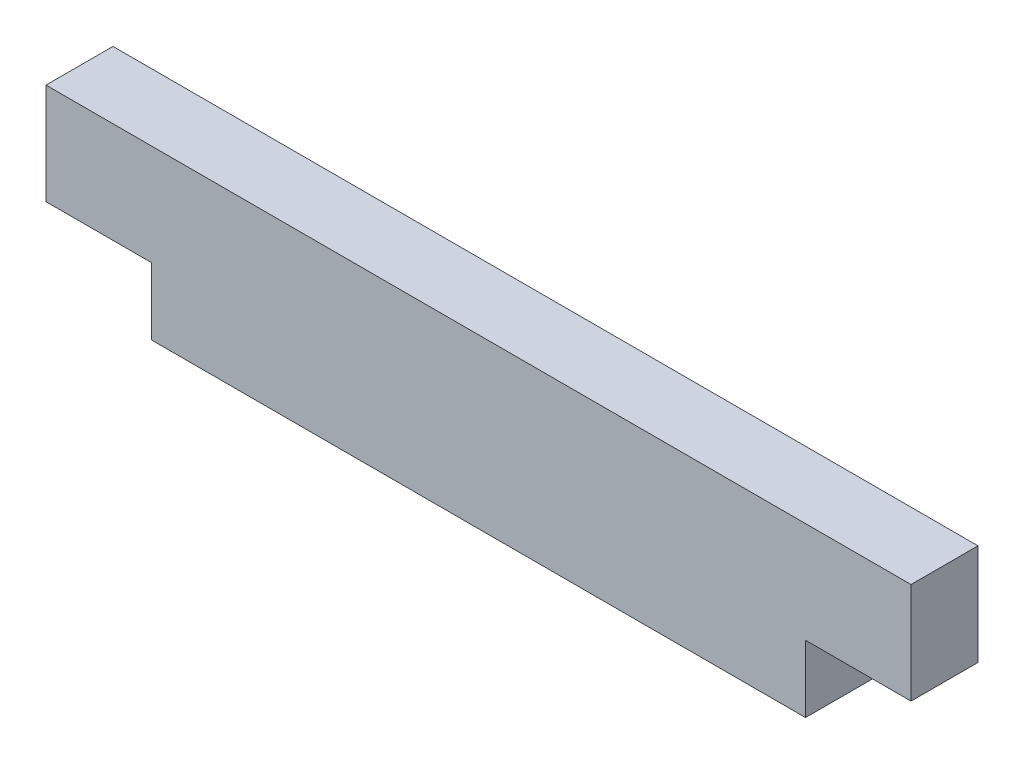
SolidWorks part; units mm, degrees
ref_plane "Front Plane" through (0, 0, 0) normal (0, 0, 1) x (1, 0, 0)
ref_plane "Top Plane" through (0, 0, 0) normal (0, 1, 0) x (1, 0, 0)
ref_plane "Right Plane" through (0, 0, 0) normal (1, 0, 0) x (0, 0, -1)
sketch "Sketch1" plane through (0, 0, 0) normal (0, 0, 1) x (1, 0, 0)
  line L1 (-20.5, -2.394) -> (20.5, -2.394)
  line L2 (-20.5, -2.394) -> (-20.5, 2.394)
  line L3 (-20.5, 2.394) -> (20.5, 2.394)
  line L4 (20.5, -2.394) -> (20.5, 2.394)
  line L5 (-20.5, -2.394) -> (20.5, 2.394) construction
  line L6 (-20.5, 2.394) -> (20.5, -2.394) construction
  line L7 (-15.5, -2.394) -> (-3.5, -2.394)
  line L8 (-15.5, -2.394) -> (-15.5, -5.569)
  line L9 (-15.5, -5.569) -> (-3.5, -5.569)
  line L10 (-3.5, -2.394) -> (-3.5, -5.569)
  line L11 (3.5, -2.394) -> (15.5, -2.394)
  line L12 (3.5, -2.394) -> (3.5, -5.569)
  line L13 (3.5, -5.569) -> (15.5, -5.569)
  line L14 (15.5, -2.394) -> (15.5, -5.569)
  point P0 (0, 0)
  dimension "D1" = 4.788
  dimension "D2" = 41
  dimension "D3" = 3.175
  dimension "D4" = 3.175
  dimension "D5" = 12
  dimension "D6" = 12
  dimension "D7" = 5
  dimension "D8" = 5
extrude "Boss-Extrude1" add sketch "Sketch1" along normal blind 3.175 contours L1 L4 L3 L2 | L10 L1 L8 L9 | L14 L1 L12 L13
sketch "Sketch2" plane through (0, 0, 3.175) normal (0, 0, 1) x (1, 0, 0)
  line L0 (-15.5, -2.394) -> (-15.5, -5.569) construction
  line L1 (-3.5, -2.394) -> (3.5, -2.394)
  line L2 (-3.5, -2.394) -> (-3.5, -5.569)
  line L3 (-3.5, -5.569) -> (3.5, -5.569)
  line L4 (3.5, -2.394) -> (3.5, -5.569)
extrude "Boss-Extrude3" add sketch "Sketch2" against normal up to surface (3.175 mm away) up to face at (0, -2.6543, 0)
